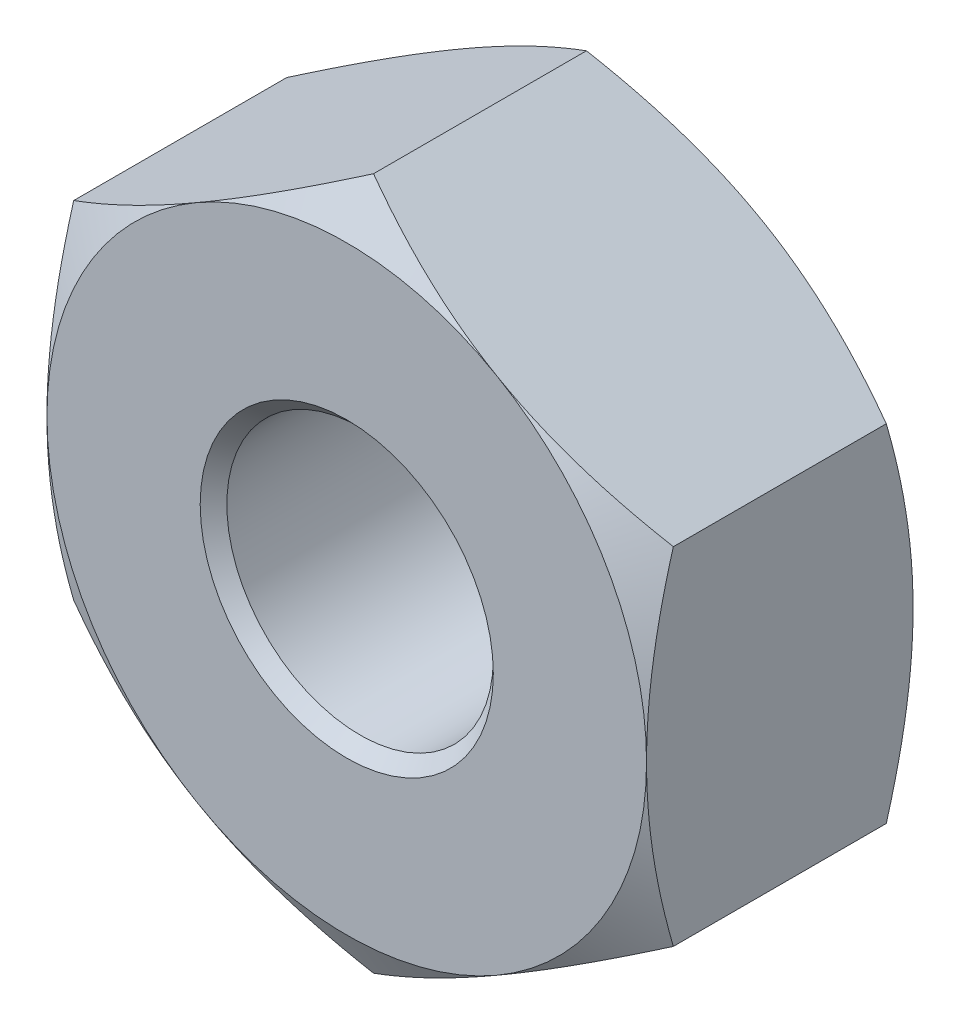
SolidWorks part; units mm, degrees
ref_plane "Alzado" through (0, 0, 0) normal (0, 0, 1) x (1, 0, 0)
ref_plane "Planta" through (0, 0, 0) normal (0, 1, 0) x (1, 0, 0)
ref_plane "Vista lateral" through (0, 0, 0) normal (1, 0, 0) x (0, 0, -1)
sketch "Croquis1" plane through (0, 0, 0) normal (0, 0, 1) x (1, 0, 0)
  line L1 (0, -2.5981) -> (2.25, -1.299)
  line L2 (2.25, -1.299) -> (2.25, 1.299)
  line L3 (2.25, 1.299) -> (0, 2.5981)
  line L4 (0, 2.5981) -> (-2.25, 1.299)
  line L5 (-2.25, 1.299) -> (-2.25, -1.299)
  line L6 (-2.25, -1.299) -> (0, -2.5981)
  circle A0 centre (0, 0) radius 2.25 construction
  circle A1 centre (0, 0) radius 1
  dimension "D1" = 2
  dimension "D2" = 4.5
extrude "Saliente-Extruir1" add sketch "Croquis1" along normal blind 2
sketch "Croquis3" plane through (0, 0, 0) normal (0, 0, 1) x (1, 0, 0)
  circle A0 centre (0, 0) radius 2.25 construction
  circle A1 centre (0, 0) radius 2.25
extrude "Cortar-Extruir1" cut sketch "Croquis3" along normal blind 2 draft 60 flip side to cut
sketch "Croquis4" plane through (0, 0, 2) normal (0, 0, 1) x (1, 0, 0)
  circle A0 centre (0, 0) radius 2.25 construction
  circle A1 centre (0, 0) radius 2.25
extrude "Cortar-Extruir4" cut sketch "Croquis4" against normal blind 2 draft 60 flip side to cut
chamfer "Chaflán1" distance 0.1 angle 45 2 edges at (1, 0, 0) (1, 0, 2)
